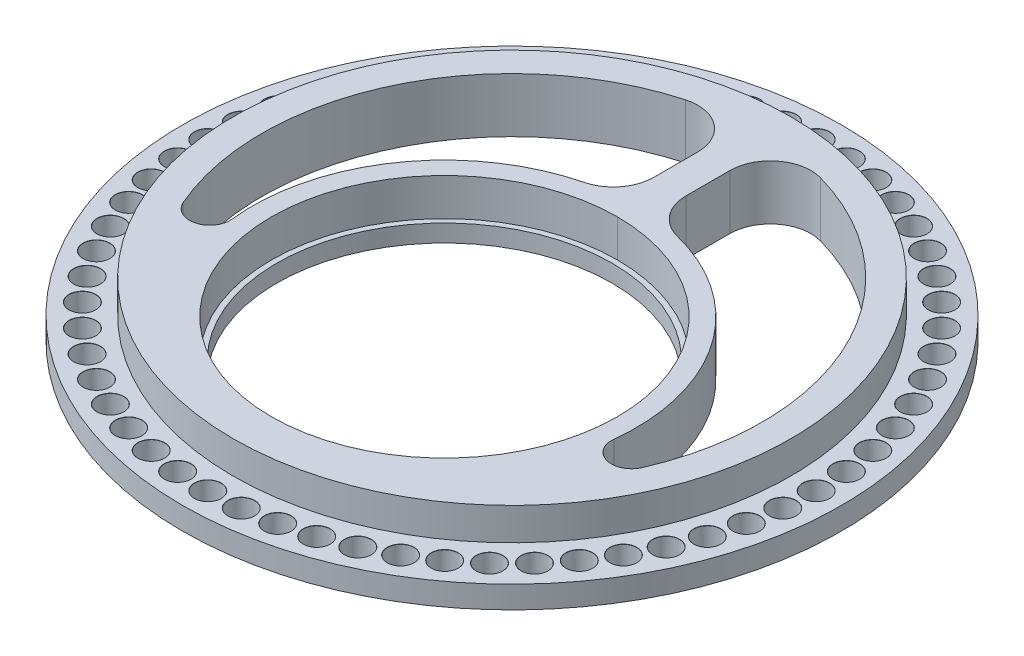
SolidWorks part; units mm, degrees
material "6061-T6 (SS)"
ref_plane "X-Y Datum" through (0, 0, 0) normal (0, 0, 1) x (1, 0, 0)
ref_plane "X-Z Datum" through (0, 0, 0) normal (0, 1, 0) x (1, 0, 0)
ref_plane "Y-Z Datum" through (0, 0, 0) normal (1, 0, 0) x (0, 0, -1)
sketch "Sketch1" plane through (0, 0, 0) normal (0, 1, 0) x (1, 0, 0)
  line L0 (0, 0) -> (0, -12.7) construction
  line L1 (0, -43.0151) -> (0, 43.0151) construction
  line L2 (0, 52.3875) -> (0, 61.9125) construction
  circle A0 centre (0, -12.7) radius 30.988
  circle A1 centre (0, 0) radius 52.3875 construction
  circle A2 centre (0, 0) radius 61.9125
  circle A3 centre (0, 0) radius 57.15 construction
  point P12 (0, 57.15)
  dimension "D2" = 61.976
  dimension "D3" = 104.775
  dimension "D4" = 123.825
  dimension "D5" = 114.3
  dimension "D1" = 12.7
extrude "Slotted-Body Extrude" add sketch "Sketch1" along normal blind 4.191
sketch "Sketch5" plane through (0, 4.191, 0) normal (0, 1, 0) x (1, 0, 0)
  circle A0 centre (0, 0) radius 52.3875 construction
  circle A1 centre (0, 0) radius 52.3875
extrude "Boss-Extrude3" add sketch "Sketch5" along normal blind 6.08
sketch "Sketch6" plane through (0, 0, 0) normal (0, -1, 0) x (1, 0, 0)
  line L0 (0, -79.2756) -> (0, 0) construction
  line L2 (3.014, -37.9067) -> (3.014, -29.6741)
  line L4 (-3.014, -37.9067) -> (-3.014, -29.6741)
  circle A0 centre (0, 12.7) radius 30.988 construction
  circle A1 centre (0, 12.7) radius 30.988 construction
  circle A2 centre (0, 12.7) radius 32.512
  arc A9 (-35.843, 16.7226) -> (-8.7792, -22.2832) centre (0, 12.7) ccw
  arc A10 (-43.1259, 18.6606) -> (-12.6921, -45.2435) centre (0, 0) ccw
  arc A11 (-43.1259, 18.6606) -> (-35.843, 16.7226) centre (-39.6292, 17.1475) cw
  arc A19 (-3.014, -29.6741) -> (-8.7792, -22.2832) centre (-10.634, -29.6741) ccw
  arc A20 (-3.014, -37.9067) -> (-12.6921, -45.2435) centre (-10.634, -37.9067) cw
  circle A21 centre (0, 0) radius 61.9125 construction
  arc A27 (43.1259, 18.6606) -> (35.843, 16.7226) centre (39.6292, 17.1475) ccw
  arc A28 (43.1259, 18.6606) -> (12.6921, -45.2435) centre (0, 0) cw
  arc A29 (3.014, -37.9067) -> (12.6921, -45.2435) centre (10.634, -37.9067) ccw
  arc A30 (3.014, -29.6741) -> (8.7792, -22.2832) centre (10.634, -29.6741) cw
  arc A31 (35.843, 16.7226) -> (8.7792, -22.2832) centre (0, 12.7) cw
  point P30 (0, 0)
  point P31 (-3.014, -23.2419)
  point P32 (0, 0)
  point P36 (-3.014, -46.8932)
  dimension "D1" = 65.024
  dimension "D2" = 7.62
  dimension "D3" = 3.81
  dimension "D4" = 46.99
  dimension "D5" = 7.62
  dimension "D6" = 36.068
  dimension "D8" = 8.2326
extrude "Cut-Extrude5" cut sketch "Sketch6" against normal through all
sketch "Sketch8" plane through (0, 0, 0) normal (0, -1, 0) x (1, 0, 0)
  circle A0 centre (0, 12.7) radius 32.512 construction
  circle A1 centre (0, 12.7) radius 32.512
  circle A2 centre (0, 12.7) radius 31.496
  dimension "D1" = 62.992
extrude "Boss-Extrude4" add sketch "Sketch8" against normal blind 3.255 separate body
hole_wizard "Ø5.0mm Dowel Hole1" positions "Sketch9" profile "Sketch10" hole size "Ø5.0" standard "ANSI Metric" end condition through all
sketch "Sketch9" plane through (0, 4.191, 0) normal (0, 1, 0) x (1, 0, 0)
  point P0 (0, 57.15)
sketch "Sketch10" plane through (0, 4.191, -57.15) normal (1, 0, 0) x (0, 0, 1)
  line L0 (0, 0) -> (0, 4.191)
  line L1 (0, 4.191) -> (2.5, 4.191)
  line L2 (2.5, 4.191) -> (2.5, 0.025)
  line L3 (2.5, 0.025) -> (2.525, 0)
  line L5 (2.525, 0) -> (0, 0)
  line L6 (-2.5, 0.025) -> (-2.525, 0) construction
  line L11 (0, -6.35) -> (0, 107.95) construction
  dimension "Thru Hole Dia." = 5
  dimension "Thru Hole Depth" = 4.191
  dimension "Near C'Sink Dia." = 5.05
  dimension "Near C'Sink Angle" = 90
pattern_circular "CirPattern1" count 60 over 360 about axis through (0, 0, 0) along (0, 1, 0) of "Ø5.0mm Dowel Hole1"
ref_point "Point1"
ref_plane "Plane1" through (0, 0, 0) normal (1, 0, 0) x (0, 0, -1)
split line "Split Line1"
curve "CompCurve1"
